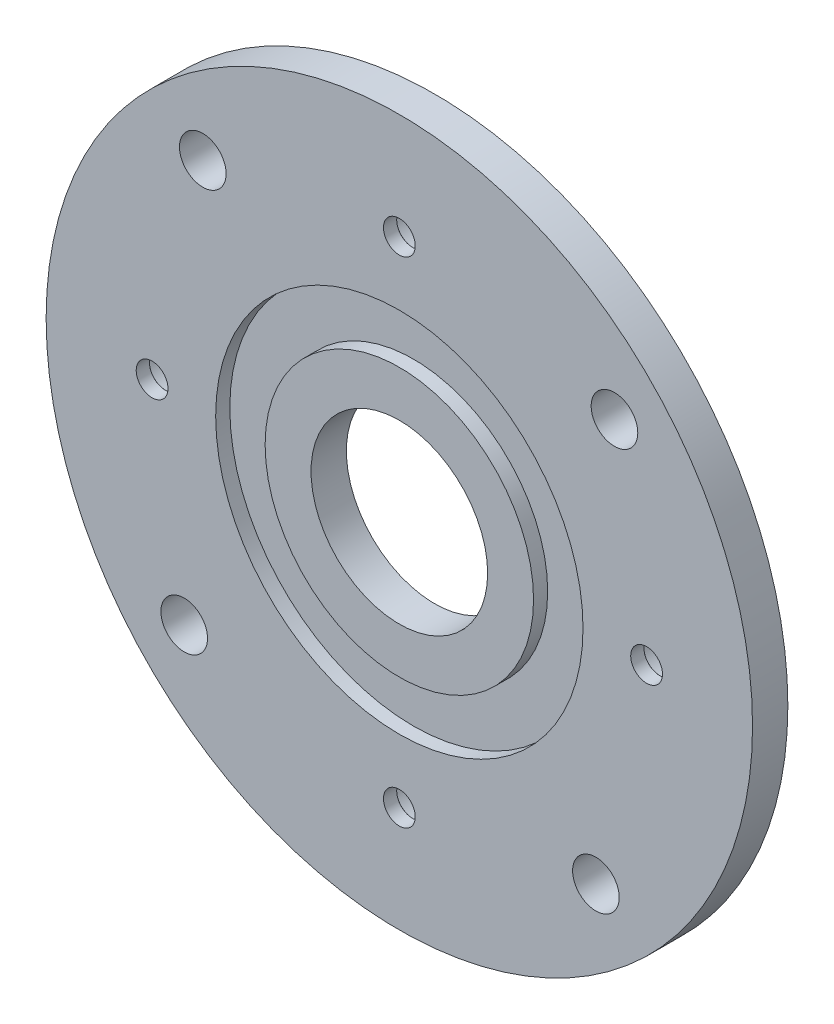
SolidWorks part; units mm, degrees
ref_plane "Plan de face" through (0, 0, 0) normal (0, 0, 1) x (1, 0, 0)
ref_plane "Plan de dessus" through (0, 0, 0) normal (0, 1, 0) x (1, 0, 0)
ref_plane "Plan de droite" through (0, 0, 0) normal (1, 0, 0) x (0, 0, -1)
sketch "Esquisse1" plane through (0, 0, 0) normal (0, 0, 1) x (1, 0, 0)
  circle A0 centre (0, 0) radius 50
  dimension "D1" = 100
extrude "Boss.-Extru.1" add sketch "Esquisse1" along normal blind 5
sketch "Esquisse2" plane through (0, 0, 5) normal (0, 0, 1) x (1, 0, 0)
  circle A0 centre (0, 0) radius 19
  circle A1 centre (0, 0) radius 26
  dimension "D1" = 38
  dimension "D2" = 52
extrude "Enlèv. mat.-Extru.1" cut sketch "Esquisse2" against normal blind 2
sketch "Esquisse3" plane through (0, 0, 5) normal (0, 0, 1) x (1, 0, 0)
  circle A0 centre (0, 0) radius 12.5
  dimension "D1" = 25
extrude "Enlèv. mat.-Extru.2" cut sketch "Esquisse3" against normal through all
sketch "Esquisse4" plane through (0, 0, 0) normal (0, 0, -1) x (-1, 0, 0)
  circle A0 centre (0, 0) radius 35 construction
  dimension "D1" = 70
hole_wizard "Chambrage pour vis à tête ronde bombée M41" positions "Esquisse6" profile "Esquisse5" counterbore size "M4" standard "Ansi Metric" end condition through all
sketch "Esquisse6" plane through (0, 0, 0) normal (0, 0, -1) x (-1, 0, 0)
  circle A0 centre (0, 0) radius 35 construction
  point P0 (0, 35)
  point P4 (35, 0)
  point P6 (0, -35)
  point P8 (-35, 0)
sketch "Esquisse5" plane through (0, 35, 0) normal (1, 0, 0) x (0, 1, 0)
  line L0 (0, 0) -> (0, 5)
  line L1 (0, 5) -> (2.25, 5)
  line L2 (2.25, 3.125) -> (2.25, 5)
  line L3 (2.25, 3.125) -> (2.275, 3.1)
  line L4 (2.275, 3.1) -> (4.5, 3.1)
  line L5 (4.5, 3.1) -> (4.5, 0)
  line L7 (0, 0) -> (4.5, 0)
  line L9 (-2.25, 3.125) -> (-2.275, 3.1) construction
  line L11 (0, -6.35) -> (0, 107.95) construction
  dimension "Diamètre du perçage jusqu'au prochain" = 4.5
  dimension "Profondeur du perçage jusqu'au prochain" = 5
  dimension "Diamètre du chambrage" = 9
  dimension "Profondeur du chambrage" = 3.1
  dimension "Diamètre du fraisage milieu" = 4.55
  dimension "Angle du fraisage milieu" = 90
hole_wizard "Dégagement M62" positions "Esquisse10" profile "Esquisse9" hole size "M6" standard "JIS" end condition through all
sketch "Esquisse10" plane through (0, 0, 5) normal (0, 0, 1) x (1, 0, 0)
  point P0 (30.4527, 27.8244)
  point P2 (-27.8244, 30.4527)
  point P4 (-30.4527, -27.8244)
  point P6 (27.8244, -30.4527)
sketch "Esquisse9" plane through (30.4527, 27.8244, 5) normal (1, 0, 0) x (0, -1, 0)
  line L0 (0, 0) -> (0, 5)
  line L1 (0, 5) -> (3.3, 5)
  line L2 (3.3, 5) -> (3.3, 0)
  line L5 (3.3, 0) -> (0, 0)
  line L11 (0, -6.35) -> (0, 107.95) construction
  dimension "Diamètre du perçage jusqu'au prochain" = 6.6
  dimension "Profondeur du perçage jusqu'au prochain" = 5
